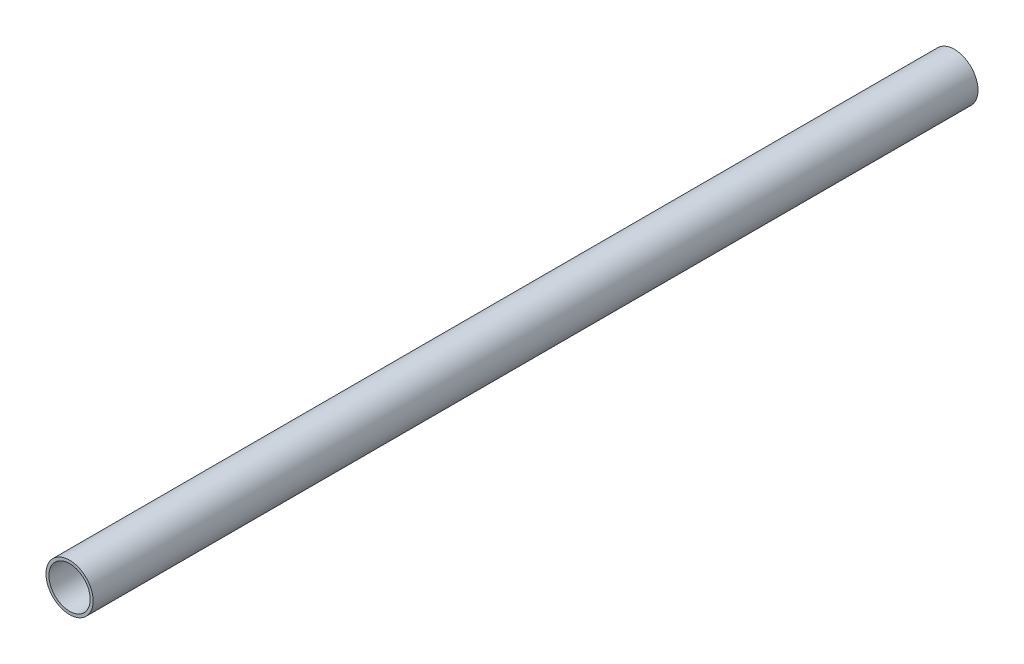
SolidWorks part; units mm, degrees
material "Poltrusion Carbon Fiber"
ref_plane "Front Plane" through (0, 0, 0) normal (0, 0, 1) x (1, 0, 0)
ref_plane "Top Plane" through (0, 0, 0) normal (0, 1, 0) x (1, 0, 0)
ref_plane "Right Plane" through (0, 0, 0) normal (1, 0, 0) x (0, 0, -1)
sketch "Эскиз1" plane through (0, 0, 0) normal (0, 0, 1) x (1, 0, 0)
  circle A0 centre (0, 0) radius 4
  circle A1 centre (0, 0) radius 3.5
  dimension "D1" = 8
  dimension "D2" = 0.5
extrude "Бобышка-Вытянуть1" add sketch "Эскиз1" along normal mid plane 150
